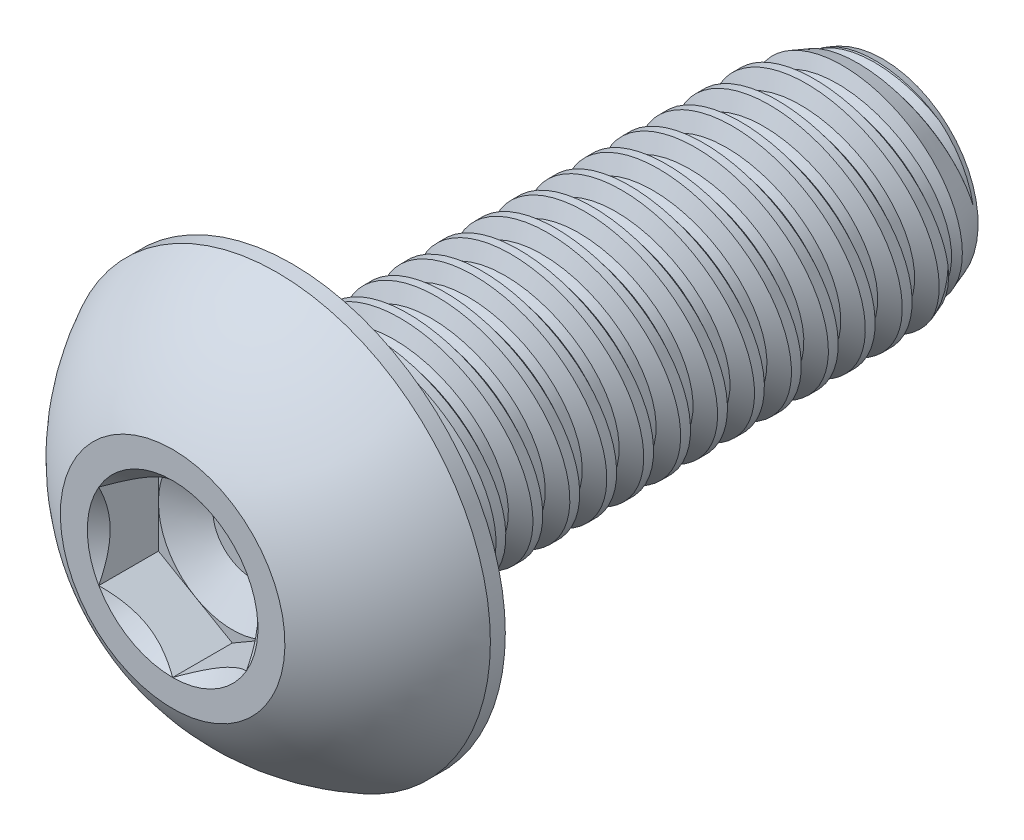
SolidWorks part; units mm, degrees
ref_plane "Front" through (0, 0, 0) normal (0, 0, 1) x (1, 0, 0)
ref_plane "Top" through (0, 0, 0) normal (0, 1, 0) x (1, 0, 0)
ref_plane "Right" through (0, 0, 0) normal (1, 0, 0) x (0, 0, -1)
sketch "Sketch1" plane through (0, 0, 0) normal (1, 0, 0) x (0, 0, -1)
  line L0 (0, 0) -> (-2.5654, 0) construction
  line L1 (0, 0) -> (12.7, 0)
  line L2 (0, 0) -> (0, 2.413)
  line L3 (0, 2.413) -> (12.7, 2.413)
  line L4 (12.7, 0) -> (12.7, 2.413)
  line L5 (0, -2.413) -> (12.7, -2.413) construction
  dimension "D1" = 12.7
  dimension "Thread Dia" = 4.826
  dimension "Length" = 12.7
  dimension "Head Height" = 2.5654
revolve "Revolve1" add sketch "Sketch1" angle 360 about L0
ref_plane "Plane1" through (0, 0, 2.5654) normal (0, 0, 1) x (1, 0, 0)
sketch "Sketch2" plane through (0, 0, 0) normal (1, 0, 0) x (0, 0, -1)
  line L0 (0, 2.413) -> (0, -2.413) construction
  line L1 (0, -2.413) -> (0.7938, -2.413) construction
  line L2 (0.7938, -2.413) -> (0, 2.413) construction
  line L3 (0, 2.413) -> (0.0979, 2.4291) construction
  line L4 (0.0979, 2.4291) -> (0.7832, 2.5418)
  line L5 (0.7832, 2.5418) -> (0.6082, 2.0776)
  line L6 (0.6082, 2.0776) -> (0.4124, 2.0454)
  line L7 (0.4124, 2.0454) -> (0.0979, 2.4291)
  line L8 (0.5103, 2.0615) -> (0.4406, 2.4855) construction
  line L9 (0, -2.413) -> (12.7, -2.413) construction
  line L10 (0, 2.413) -> (12.7, 2.413) construction
  line L12 (0.4525, 2.413) -> (1.2462, -2.413) construction
  line L13 (0, -0.1397) -> (1.6987, 0.1397) construction
  line L15 (0, 0) -> (0, 2.413) construction
  point P19 (0.8494, 0)
  dimension "D1" = 60
  dimension "Thread Pitch" = 0.7937
  dimension "D2" = 0.0992
  dimension "D3" = 0.1984
  dimension "D4" = 0.7937
revolve "Cut-Revolve1" cut sketch "Sketch2" angle 360 about L13
sketch "Sketch3" plane through (0, 0, 0) normal (1, 0, 0) x (0, 0, -1)
  line L0 (12.7, 2.0454) -> (11.6901, 2.413)
  line L1 (11.6901, 2.413) -> (12.7, 2.413)
  line L2 (12.7, 2.413) -> (12.7, 2.0454)
  line L3 (0, 2.413) -> (12.7, 2.413) construction
  line L4 (12.7, 0) -> (12.7, 2.413) construction
  line L5 (11.6901, 0) -> (0, 0) construction
  line L6 (11.6901, 2.413) -> (11.6901, -2.413) construction
  line L7 (0, -2.413) -> (12.7, -2.413) construction
  dimension "D1" = 20
  dimension "D2" = 4.826
revolve "Cut-Revolve2" cut sketch "Sketch3" angle 360 about L5
pattern_linear "LPattern1" count 16 spacing 0.7937 along (0, 0, -1) of "Cut-Revolve1"
pattern_linear "LPattern2" count 2 spacing 0.7937 along (0, 0, 1) of "Cut-Revolve1"
sketch "Sketch4" plane through (0, 0, 0) normal (0, 0, 1) x (1, 0, 0)
  circle A0 centre (0, 0) radius 4.5847
  dimension "Head Dia" = 9.1694
extrude "Extrude1" add sketch "Sketch4" along normal up to surface (2.5654 mm away) up to plane "Plane1"
sketch "Sketch9" plane through (0, 0, 0) normal (1, 0, 0) x (0, 0, -1)
  line L0 (0, 4.5847) -> (-0.3207, 4.5847)
  line L1 (0, 4.5847) -> (0, 4.9054)
  line L2 (0, 4.9054) -> (-2.8861, 4.9054)
  line L3 (0, 0) -> (-2.5654, 0) construction
  line L4 (-2.8861, 4.9054) -> (-2.8861, 2.413)
  line L5 (-2.8861, 2.413) -> (-2.5654, 2.413)
  line L6 (0, 0) -> (0, 2.413) construction
  line L10 (0, 4.5847) -> (-2.5654, 4.5847) construction
  line L11 (0, 2.413) -> (12.7, 2.413) construction
  line L12 (-2.5654, 4.5847) -> (-2.5654, -4.5847) construction
  arc A0 (-2.5654, 2.413) -> (-0.3207, 4.5847) centre (1.942, 0) cw
  dimension "Side Head Height" = 0.3207
revolve "Cut-Revolve3" cut sketch "Sketch9" angle 360 about L3
sketch "Sketch6" plane through (0, 0, 2.5654) normal (0, 0, 1) x (1, 0, 0)
  line L1 (0, -1.8331) -> (1.5875, -0.9165)
  line L2 (1.5875, -0.9165) -> (1.5875, 0.9165)
  line L3 (1.5875, 0.9165) -> (0, 1.8331)
  line L4 (0, 1.8331) -> (-1.5875, 0.9165)
  line L5 (-1.5875, 0.9165) -> (-1.5875, -0.9165)
  line L6 (-1.5875, -0.9165) -> (0, -1.8331)
  circle A0 centre (0, 0) radius 1.5875 construction
  dimension "Hex" = 3.175
extrude "Cut-Extrude1" cut sketch "Sketch6" against normal blind 1.2827
sketch "Sketch7" plane through (0, 0, 2.5654) normal (0, 0, 1) x (1, 0, 0)
  circle A0 centre (0, 0) radius 1.8331
extrude "Cut-Extrude4" cut sketch "Sketch7" against normal blind 1.2827 draft 45
sketch "Sketch8" plane through (0, 0, 1.2827) normal (0, 0, 1) x (1, 0, 0)
  circle A0 centre (0, 0) radius 1.5875 construction
  circle A1 centre (0, 0) radius 1.5875
extrude "Cut-Extrude5" cut sketch "Sketch8" against normal blind 0.4276 draft 60
equation "\"D2@Sketch2\"=\"Thread Pitch@Sketch2\"/8"
equation "\"D3@Sketch2\"=\"Thread Pitch@Sketch2\"/4"
equation "\"D4@Sketch2\"=\"Thread Pitch@Sketch2\""
equation "\"D3@LPattern1\"=\"Thread Pitch@Sketch2\""
equation "\"D1@Cut-Extrude1\"=\"Head Height@Sketch1\"/2"
equation "\"D1@Cut-Extrude4\"=\"D1@Cut-Extrude1\""
equation "\"D1@Cut-Extrude5\"=\"D1@Cut-Extrude1\"/3"
equation "\"D1@LPattern1\"=\"D1@Sketch1\"/\"Thread Pitch@Sketch2\""
equation "\"D3@LPattern2\"=\"Thread Pitch@Sketch2\""
equation "\"Side Head Height@Sketch9\"=\"Head Height@Sketch1\"/8"
